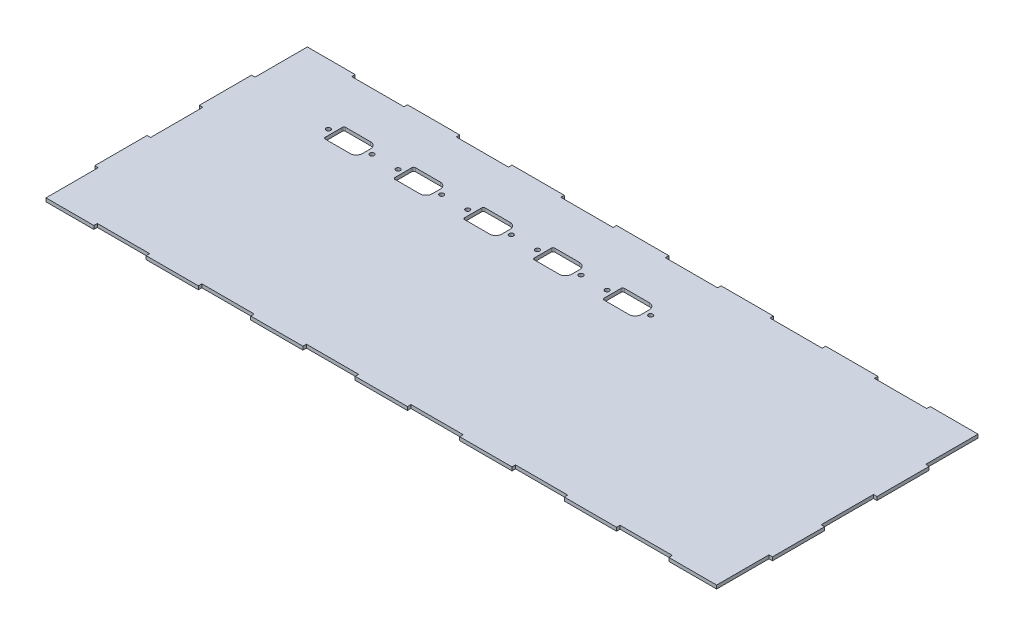
SolidWorks part; units mm, degrees
ref_plane "Front Plane" through (0, 0, 0) normal (0, 0, 1) x (1, 0, 0)
ref_plane "Top Plane" through (0, 0, 0) normal (0, 1, 0) x (1, 0, 0)
ref_plane "Right Plane" through (0, 0, 0) normal (1, 0, 0) x (0, 0, -1)
sketch "Sketch1" plane through (0, 0, 0) normal (0, 1, 0) x (1, 0, 0)
  line L0 (192.1586, 82.0164) -> (164.7086, 82.0164)
  line L1 (164.7086, 82.0164) -> (164.7086, 80.0164)
  line L2 (164.7086, 80.0164) -> (134.7086, 80.0164)
  line L3 (134.7086, 80.0164) -> (134.7086, 82.0164)
  line L4 (134.7086, 82.0164) -> (104.7086, 82.0164)
  line L5 (104.7086, 82.0164) -> (104.7086, 80.0164)
  line L6 (104.7086, 80.0164) -> (74.7086, 80.0164)
  line L7 (74.7086, 80.0164) -> (74.7086, 82.0164)
  line L8 (74.7086, 82.0164) -> (44.7086, 82.0164)
  line L9 (44.7086, 82.0164) -> (44.7086, 80.0164)
  line L10 (44.7086, 80.0164) -> (14.7086, 80.0164)
  line L11 (14.7086, 80.0164) -> (14.7086, 82.0164)
  line L12 (14.7086, 82.0164) -> (-15.2914, 82.0164)
  line L13 (-15.2914, 82.0164) -> (-15.2914, 80.0164)
  line L14 (-15.2914, 80.0164) -> (-45.2914, 80.0164)
  line L15 (-45.2914, 80.0164) -> (-45.2914, 82.0164)
  line L16 (-45.2914, 82.0164) -> (-75.2914, 82.0164)
  line L17 (-75.2914, 82.0164) -> (-75.2914, 80.0164)
  line L18 (-75.2914, 80.0164) -> (-105.2914, 80.0164)
  line L19 (-105.2914, 80.0164) -> (-105.2914, 82.0164)
  line L20 (-105.2914, 82.0164) -> (-135.2914, 82.0164)
  line L21 (-135.2914, 82.0164) -> (-135.2914, 80.0164)
  line L22 (-135.2914, 80.0164) -> (-165.2914, 80.0164)
  line L23 (-165.2914, 80.0164) -> (-165.2914, 82.0164)
  line L24 (-165.2914, 82.0164) -> (-192.7414, 82.0164)
  line L25 (-192.7414, 82.0164) -> (-192.7414, 80.0164)
  line L26 (-192.7414, 80.0164) -> (-192.7414, 52.0164)
  line L27 (-192.7414, 52.0164) -> (-194.7414, 52.0164)
  line L28 (-194.7414, 52.0164) -> (-194.7414, 22.0164)
  line L29 (-194.7414, 22.0164) -> (-192.7414, 22.0164)
  line L30 (-192.7414, 22.0164) -> (-192.7414, -7.9836)
  line L31 (-192.7414, -7.9836) -> (-194.7414, -7.9836)
  line L32 (-194.7414, -7.9836) -> (-194.7414, -37.9836)
  line L33 (-194.7414, -37.9836) -> (-192.7414, -37.9836)
  line L34 (-192.7414, -37.9836) -> (-192.7414, -65.9836)
  line L35 (-192.7414, -65.9836) -> (-192.7414, -67.9836)
  line L36 (-192.7414, -67.9836) -> (-165.2914, -67.9836)
  line L37 (-165.2914, -67.9836) -> (-165.2914, -65.9836)
  line L38 (-165.2914, -65.9836) -> (-135.2914, -65.9836)
  line L39 (-135.2914, -65.9836) -> (-135.2914, -67.9836)
  line L40 (-135.2914, -67.9836) -> (-105.2914, -67.9836)
  line L41 (-105.2914, -67.9836) -> (-105.2914, -65.9836)
  line L42 (-105.2914, -65.9836) -> (-75.2914, -65.9836)
  line L43 (-75.2914, -65.9836) -> (-75.2914, -67.9836)
  line L44 (-75.2914, -67.9836) -> (-45.2914, -67.9836)
  line L45 (-45.2914, -67.9836) -> (-45.2914, -65.9836)
  line L46 (-45.2914, -65.9836) -> (-15.2914, -65.9836)
  line L47 (-15.2914, -65.9836) -> (-15.2914, -67.9836)
  line L48 (-15.2914, -67.9836) -> (14.7086, -67.9836)
  line L49 (14.7086, -67.9836) -> (14.7086, -65.9836)
  line L50 (14.7086, -65.9836) -> (44.7086, -65.9836)
  line L51 (44.7086, -65.9836) -> (44.7086, -67.9836)
  line L52 (44.7086, -67.9836) -> (74.7086, -67.9836)
  line L53 (74.7086, -67.9836) -> (74.7086, -65.9836)
  line L54 (74.7086, -65.9836) -> (104.7086, -65.9836)
  line L55 (104.7086, -65.9836) -> (104.7086, -67.9836)
  line L56 (104.7086, -67.9836) -> (134.7086, -67.9836)
  line L57 (134.7086, -67.9836) -> (134.7086, -65.9836)
  line L58 (134.7086, -65.9836) -> (164.7086, -65.9836)
  line L59 (164.7086, -65.9836) -> (164.7086, -67.9836)
  line L60 (164.7086, -67.9836) -> (192.1586, -67.9836)
  line L61 (192.1586, -67.9836) -> (192.1586, -65.9836)
  line L62 (192.1586, -65.9836) -> (192.1586, -37.9836)
  line L63 (192.1586, -37.9836) -> (194.1586, -37.9836)
  line L64 (194.1586, -37.9836) -> (194.1586, -7.9836)
  line L65 (194.1586, -7.9836) -> (192.1586, -7.9836)
  line L66 (192.1586, -7.9836) -> (192.1586, 22.0164)
  line L67 (192.1586, 22.0164) -> (194.1586, 22.0164)
  line L68 (194.1586, 22.0164) -> (194.1586, 52.0164)
  line L69 (194.1586, 52.0164) -> (192.1586, 52.0164)
  line L70 (192.1586, 52.0164) -> (192.1586, 80.0164)
  line L71 (192.1586, 80.0164) -> (192.1586, 82.0164)
  point P657 (0, 0)
extrude "Boss-Extrude1" add sketch "Sketch1" along normal blind 2
sketch "Sketch3" plane through (0, 2, 0) normal (0, 1, 0) x (1, 0, 0)
  line L0 (-127.4664, 41.3164) -> (-141.7414, 41.3164)
  line L1 (-141.7414, 53.0164) -> (-127.4664, 53.0164)
  line L2 (-142.7414, 42.3164) -> (-142.7414, 52.0164)
  line L3 (-123.9414, 44.8414) -> (-123.9414, 49.4914)
  line L4 (-142.7414, 42.3164) -> (-133.3414, 42.3164) construction
  line L5 (-133.3414, 47.1664) -> (-145.8414, 47.1664) construction
  line L18 (-133.3414, 47.1664) -> (-120.8414, 47.1664) construction
  line L23 (-87.4664, 41.3164) -> (-101.7414, 41.3164)
  line L24 (-101.7414, 53.0164) -> (-87.4664, 53.0164)
  line L25 (-102.7414, 42.3164) -> (-102.7414, 52.0164)
  line L30 (-83.9414, 44.8414) -> (-83.9414, 49.4914)
  line L31 (-102.7414, 42.3164) -> (-93.3414, 42.3164) construction
  line L32 (-93.3414, 47.1664) -> (-105.8414, 47.1664) construction
  line L37 (-93.3414, 47.1664) -> (-80.8414, 47.1664) construction
  line L38 (-47.4664, 41.3164) -> (-61.7414, 41.3164)
  line L39 (-61.7414, 53.0164) -> (-47.4664, 53.0164)
  line L44 (-62.7414, 42.3164) -> (-62.7414, 52.0164)
  line L45 (-43.9414, 44.8414) -> (-43.9414, 49.4914)
  line L46 (-62.7414, 42.3164) -> (-53.3414, 42.3164) construction
  line L47 (-53.3414, 47.1664) -> (-65.8414, 47.1664) construction
  line L48 (-53.3414, 47.1664) -> (-40.8414, 47.1664) construction
  line L49 (-7.4664, 41.3164) -> (-21.7414, 41.3164)
  line L50 (-21.7414, 53.0164) -> (-7.4664, 53.0164)
  line L51 (-22.7414, 42.3164) -> (-22.7414, 52.0164)
  line L52 (-3.9414, 44.8414) -> (-3.9414, 49.4914)
  line L53 (-22.7414, 42.3164) -> (-13.3414, 42.3164) construction
  line L54 (-13.3414, 47.1664) -> (-25.8414, 47.1664) construction
  line L55 (-13.3414, 47.1664) -> (-0.8414, 47.1664) construction
  line L56 (32.5336, 41.3164) -> (18.2586, 41.3164)
  line L57 (18.2586, 53.0164) -> (32.5336, 53.0164)
  line L58 (17.2586, 42.3164) -> (17.2586, 52.0164)
  line L59 (36.0586, 44.8414) -> (36.0586, 49.4914)
  line L60 (17.2586, 42.3164) -> (26.6586, 42.3164) construction
  line L61 (26.6586, 47.1664) -> (14.1586, 47.1664) construction
  line L62 (26.6586, 47.1664) -> (39.1586, 47.1664) construction
  arc A0 (-123.9414, 44.8414) -> (-127.4664, 41.3164) centre (-127.4664, 44.8414) cw
  arc A1 (-123.9414, 49.4914) -> (-127.4664, 53.0164) centre (-127.4664, 49.4914) ccw
  arc A2 (-141.7414, 41.3164) -> (-142.7414, 42.3164) centre (-141.7414, 42.3164) cw
  arc A3 (-142.7414, 52.0164) -> (-141.7414, 53.0164) centre (-141.7414, 52.0164) cw
  circle A16 centre (-145.8414, 47.1664) radius 1.25
  circle A17 centre (-120.8414, 47.1664) radius 1.25
  arc A42 (-83.9414, 44.8414) -> (-87.4664, 41.3164) centre (-87.4664, 44.8414) cw
  arc A43 (-83.9414, 49.4914) -> (-87.4664, 53.0164) centre (-87.4664, 49.4914) ccw
  arc A44 (-101.7414, 41.3164) -> (-102.7414, 42.3164) centre (-101.7414, 42.3164) cw
  arc A45 (-102.7414, 52.0164) -> (-101.7414, 53.0164) centre (-101.7414, 52.0164) cw
  circle A46 centre (-105.8414, 47.1664) radius 1.25
  circle A47 centre (-80.8414, 47.1664) radius 1.25
  arc A48 (-43.9414, 44.8414) -> (-47.4664, 41.3164) centre (-47.4664, 44.8414) cw
  arc A49 (-43.9414, 49.4914) -> (-47.4664, 53.0164) centre (-47.4664, 49.4914) ccw
  arc A50 (-61.7414, 41.3164) -> (-62.7414, 42.3164) centre (-61.7414, 42.3164) cw
  arc A51 (-62.7414, 52.0164) -> (-61.7414, 53.0164) centre (-61.7414, 52.0164) cw
  circle A52 centre (-65.8414, 47.1664) radius 1.25
  circle A53 centre (-40.8414, 47.1664) radius 1.25
  arc A54 (-3.9414, 44.8414) -> (-7.4664, 41.3164) centre (-7.4664, 44.8414) cw
  arc A55 (-3.9414, 49.4914) -> (-7.4664, 53.0164) centre (-7.4664, 49.4914) ccw
  arc A56 (-21.7414, 41.3164) -> (-22.7414, 42.3164) centre (-21.7414, 42.3164) cw
  arc A57 (-22.7414, 52.0164) -> (-21.7414, 53.0164) centre (-21.7414, 52.0164) cw
  circle A58 centre (-25.8414, 47.1664) radius 1.25
  circle A59 centre (-0.8414, 47.1664) radius 1.25
  arc A60 (36.0586, 44.8414) -> (32.5336, 41.3164) centre (32.5336, 44.8414) cw
  arc A61 (36.0586, 49.4914) -> (32.5336, 53.0164) centre (32.5336, 49.4914) ccw
  arc A62 (18.2586, 41.3164) -> (17.2586, 42.3164) centre (18.2586, 42.3164) cw
  arc A63 (17.2586, 52.0164) -> (18.2586, 53.0164) centre (18.2586, 52.0164) cw
  circle A64 centre (14.1586, 47.1664) radius 1.25
  circle A65 centre (39.1586, 47.1664) radius 1.25
  dimension "D7" = 2.5
  dimension "D8" = 2.5
  dimension "D1" = 14.275
  dimension "D2" = 11.7
  dimension "D3" = 9.4
  dimension "D4" = 12.5
  dimension "D6" = 12.5
extrude "Cut-Extrude1" cut sketch "Sketch3" against normal blind 2
